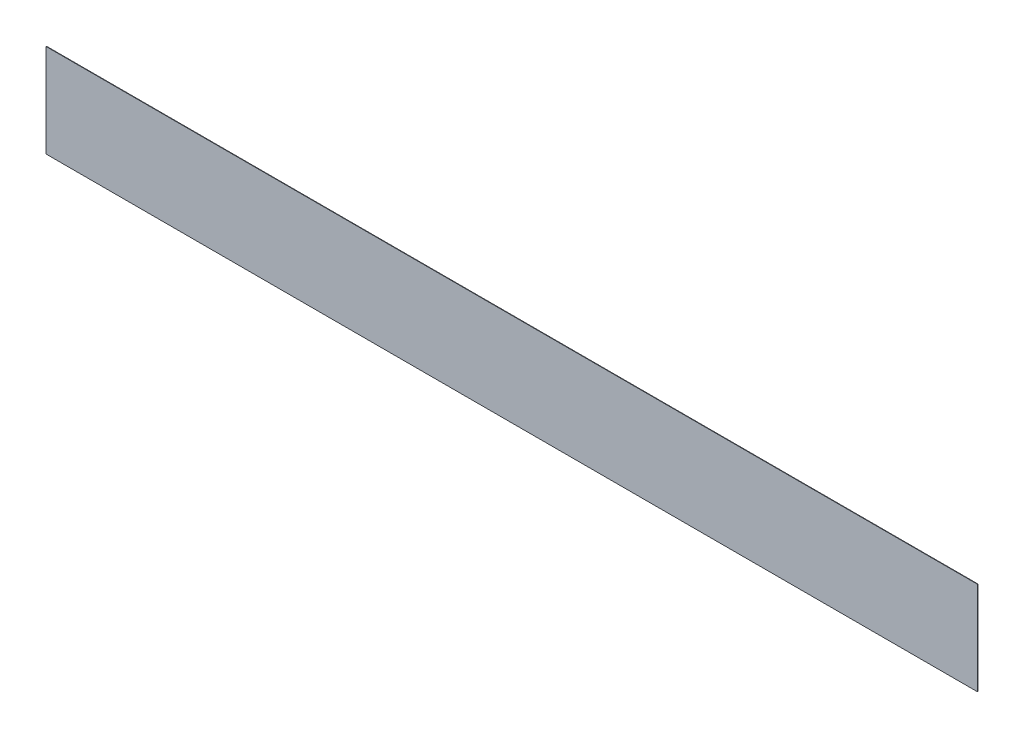
SolidWorks part; units mm, degrees
ref_plane "Front Plane" through (0, 0, 0) normal (0, 0, 1) x (1, 0, 0)
ref_plane "Top Plane" through (0, 0, 0) normal (0, 1, 0) x (1, 0, 0)
ref_plane "Right Plane" through (0, 0, 0) normal (1, 0, 0) x (0, 0, -1)
sketch "Sketch1" plane through (0, 0, 0) normal (0, 0, 1) x (1, 0, 0)
  line L1 (-2000, 2000) -> (38000, 2000)
  line L2 (-2000, 2000) -> (-2000, -2000)
  line L3 (-2000, -2000) -> (38000, -2000)
  line L4 (38000, 2000) -> (38000, -2000)
  dimension "D1" = 4000
  dimension "D2" = 40000
  dimension "D3" = 2000
  dimension "D4" = 2000
extrude "Boss-Extrude1" add sketch "Sketch1" against normal blind 20
